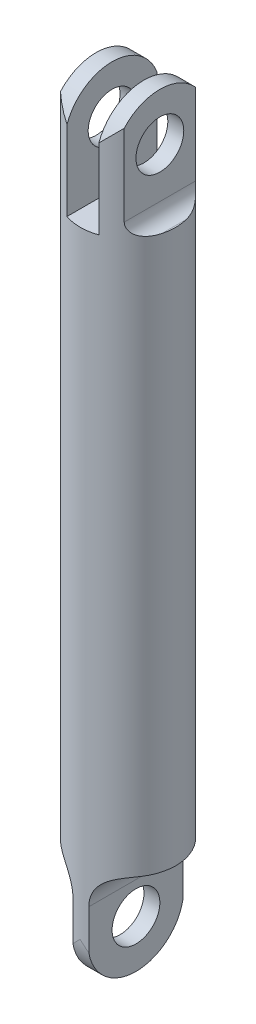
SolidWorks part; units mm, degrees
ref_plane "Front Plane" through (0, 0, 0) normal (0, 0, 1) x (1, 0, 0)
ref_plane "Top Plane" through (0, 0, 0) normal (0, 1, 0) x (1, 0, 0)
ref_plane "Right Plane" through (0, 0, 0) normal (1, 0, 0) x (0, 0, -1)
sketch "Sketch1" plane through (0, 0, 0) normal (0, 1, 0) x (1, 0, 0)
  circle A0 centre (0, 0) radius 30
  dimension "D1" = 60
extrude "Boss-Extrude1" add sketch "Sketch1" along normal mid plane 487
sketch "Sketch3" plane through (0, 243.5, 0) normal (0, 1, 0) x (1, 0, 0)
  line L0 (-10, 28.2843) -> (-10, -28.2843)
  line L1 (10, 28.2843) -> (10, -28.2843)
  line L2 (-20, 22.3607) -> (-20, -22.3607)
  line L3 (20, 22.3607) -> (20, -22.3607)
  line L4 (-20, 28.2843) -> (-20, -28.2843) construction
  line L6 (20, 28.2843) -> (20, -28.2843) construction
  circle A0 centre (0, 0) radius 30 construction
  arc A1 (10, 28.2843) -> (-10, 28.2843) centre (0, 0) ccw
  arc A2 (20, -22.3607) -> (20, 22.3607) centre (0, 0) ccw
  arc A3 (-20, 22.3607) -> (-20, -22.3607) centre (0, 0) ccw
  arc A4 (-10, -28.2843) -> (10, -28.2843) centre (0, 0) ccw
  dimension "D1" = 10
  dimension "D2" = 10
  dimension "D3" = 10
  dimension "D4" = 10
extrude "Cut-Extrude1" cut sketch "Sketch3" against normal blind 70
fillet "Fillet1" radius 9 1 edges at (-20, 173.5, 0)
fillet "Fillet2" radius 9 1 edges at (20, 173.5, 0)
sketch "Sketch4" plane through (20, 0, 0) normal (1, 0, 0) x (0, 0, -1)
  line L0 (22.3607, 243.5) -> (-22.3607, 243.5) construction
  circle A0 centre (0, 213.5) radius 15
  dimension "D1" = 30
  dimension "D2" = 30
extrude "Cut-Extrude2" cut sketch "Sketch4" against normal blind 70
sketch "Sketch6" plane through (0, 0, 0) normal (1, 0, 0) x (0, 0, -1)
  line L1 (-28.2843, 243.5) -> (28.2843, 243.5)
  line L6 (28.2843, 243.5) -> (28.2843, 223.5)
  line L7 (28.2843, 173.5) -> (28.2843, 243.5) construction
  line L8 (-28.2843, 243.5) -> (-28.2843, 223.5)
  line L9 (-28.2843, 173.5) -> (-28.2843, 243.5) construction
  arc A0 (28.2843, 223.5) -> (-28.2843, 223.5) centre (0, 213.5) ccw
  dimension "D1" = 60
  dimension "D2" = 56.5685
extrude "Cut-Extrude3" cut sketch "Sketch6" against normal blind 70 and the other way blind 70 contours A0 L1 L8 | A0 L6 L1
sketch "Sketch7" plane through (0, -243.5, 0) normal (0, -1, 0) x (1, 0, 0)
  line L0 (-5, 29.5804) -> (-5, -29.5804)
  line L1 (0, -33) -> (0, 33) construction
  line L2 (5, 29.5804) -> (5, -29.5804)
  circle A0 centre (0, 0) radius 30 construction
  arc A1 (-5, 29.5804) -> (-5, -29.5804) centre (0, 0) ccw
  arc A2 (5, -29.5804) -> (5, 29.5804) centre (0, 0) ccw
  dimension "D1" = 5
extrude "Cut-Extrude4" cut sketch "Sketch7" against normal blind 70
sketch "Sketch8" plane through (5, 0, 0) normal (1, 0, 0) x (0, 0, -1)
  line L0 (-29.5804, -243.5) -> (29.5804, -243.5) construction
  circle A0 centre (0, -213.5) radius 15
  dimension "D1" = 30
  dimension "D2" = 30
extrude "Cut-Extrude5" cut sketch "Sketch8" against normal blind 60
sketch "Sketch10" plane through (0, 0, 0) normal (1, 0, 0) x (0, 0, -1)
  line L0 (-30, -213.5) -> (-30, -243.5)
  line L1 (-30, -243.5) -> (30, -243.5)
  line L2 (30, -243.5) -> (30, -213.5)
  circle A0 centre (0, -213.5) radius 30
  dimension "D1" = 60
extrude "Cut-Extrude8" cut sketch "Sketch10" against normal blind 60 and the other way blind 60 contours A0 L1 L2 | A0 L0 L1
fillet "Fillet3" radius 20 1 edges at (5, -173.5, 0)
fillet "Fillet4" radius 20 1 edges at (-5, -173.5, 0)
